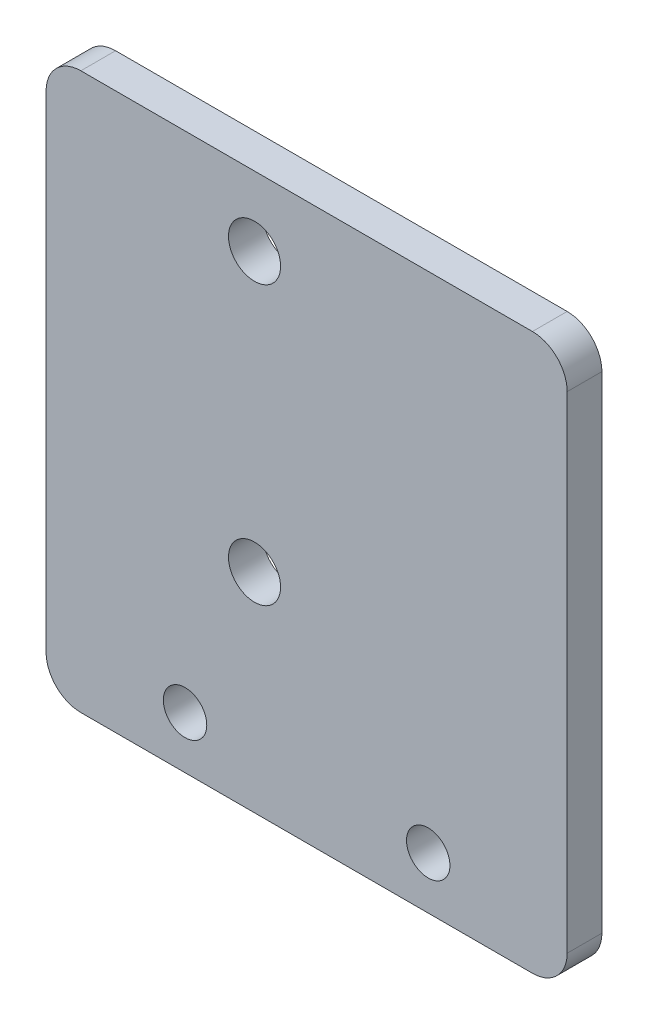
SolidWorks part; units mm, degrees
ref_plane "正面" through (0, 0, 0) normal (0, 0, 1) x (1, 0, 0)
ref_plane "平面" through (0, 0, 0) normal (0, 1, 0) x (1, 0, 0)
ref_plane "右側面" through (0, 0, 0) normal (1, 0, 0) x (0, 0, -1)
sketch "ｽｹｯﾁ1" plane through (0, 0, 0) normal (0, 0, 1) x (1, 0, 0)
  line L1 (0, 0) -> (30, 0)
  line L2 (0, 0) -> (0, 32)
  line L3 (0, 32) -> (30, 32)
  line L4 (30, 0) -> (30, 32)
  circle A0 centre (8, 3) radius 1.25
  circle A1 centre (22, 3) radius 1.25
  circle A2 centre (12, 28) radius 1.5
  circle A3 centre (12, 12) radius 1.5
  dimension "D3" = 2.5
  dimension "D13" = 3
  dimension "D1" = 30
  dimension "D2" = 32
  dimension "D5" = 8
  dimension "D6" = 8
  dimension "D7" = 3
  dimension "D8" = 3
  dimension "D9" = 4
  dimension "D10" = 16
  dimension "D11" = 12
  dimension "D12" = 12
extrude "ﾎﾞｽ - 押し出し1" add sketch "ｽｹｯﾁ1" along normal blind 2
fillet "ﾌｨﾚｯﾄ1" radius 2 4 edges at (0, 0, 1) (30, 0, 1) (30, 32, 1) (0, 32, 1)
